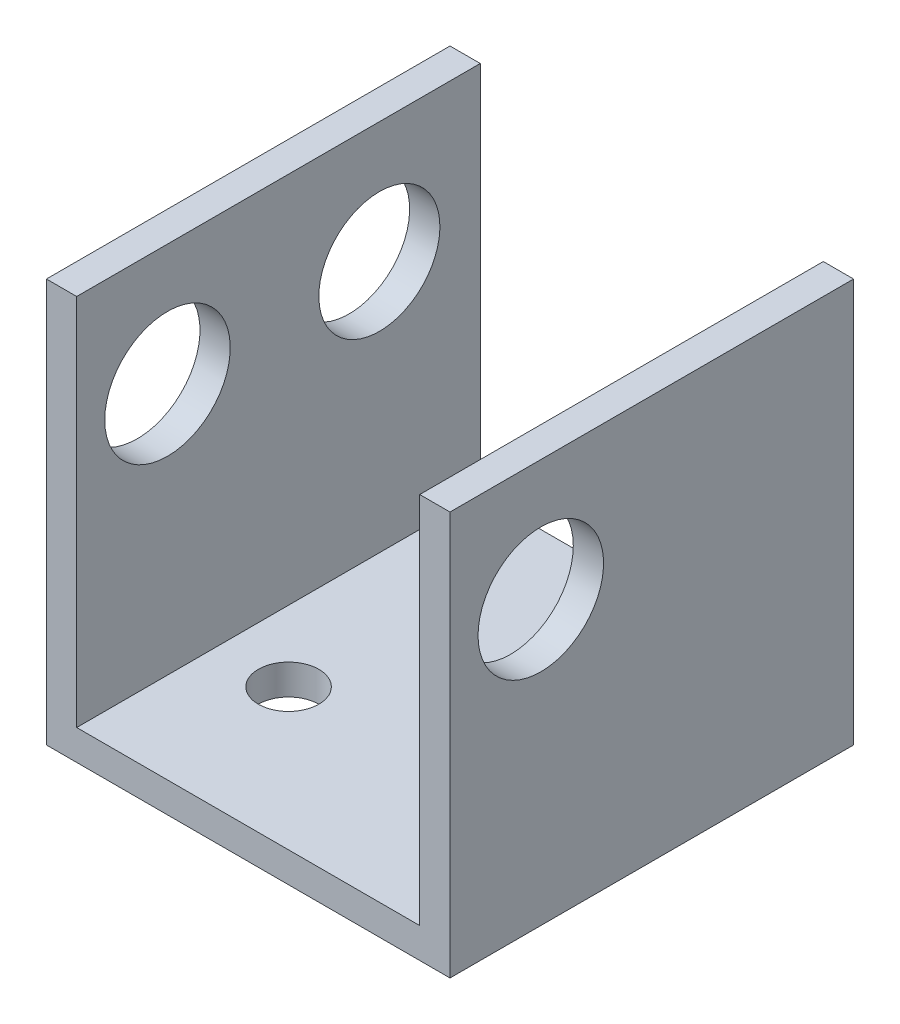
SolidWorks part; units mm, degrees
ref_plane "Plan de face" through (0, 0, 0) normal (0, 0, 1) x (1, 0, 0)
ref_plane "Plan de dessus" through (0, 0, 0) normal (0, 1, 0) x (1, 0, 0)
ref_plane "Plan de droite" through (0, 0, 0) normal (1, 0, 0) x (0, 0, -1)
sketch "Esquisse1" plane through (0, 0, 0) normal (0, 0, 1) x (1, 0, 0)
  line L0 (-31.1486, 3.3838) -> (-29.6486, 3.3838)
  line L1 (-29.6486, 3.3838) -> (-29.6486, -15.1162)
  line L2 (-29.6486, -15.1162) -> (-12.6486, -15.1162)
  line L3 (-11.1486, 3.3838) -> (-11.1486, -16.6162)
  line L4 (-11.1486, -16.6162) -> (-31.1486, -16.6162)
  line L5 (-31.1486, -16.6162) -> (-31.1486, 3.3838)
  line L6 (-12.6486, -15.1162) -> (-12.6486, 3.3838)
  line L7 (-12.6486, 3.3838) -> (-11.1486, 3.3838)
  dimension "D1" = 20
  dimension "D2" = 1.5
  dimension "D3" = 1.5
  dimension "D4" = 20
  dimension "D5" = 1.5
  dimension "D6" = 20
extrude "Extrusion1" add sketch "Esquisse1" along normal blind 20
sketch "Esquisse2" plane through (0, -15.1162, 0) normal (0, 1, 0) x (-1, 0, 0)
  line L1 (31.1486, 20) -> (31.1486, 0) construction
  line L2 (12.6486, 20) -> (29.6486, 20) construction
  line L4 (12.6486, 0) -> (29.6486, 0) construction
  line L5 (11.1486, 20) -> (11.1486, 0) construction
  circle A0 centre (26.1486, 13) radius 1.5
  circle A2 centre (16.1486, 7) radius 1.5
  dimension "D4" = 7
  dimension "D1" = 5
  dimension "D2" = 5
  dimension "D3" = 7
extrude "Extrusion2" cut sketch "Esquisse2" against normal through all
sketch "Esquisse4" plane through (-29.6486, 0, 0) normal (1, 0, 0) x (0, 0, -1)
  line L3 (0, -15.1162) -> (0, 3.3838) construction
  line L4 (-20, 3.3838) -> (0, 3.3838) construction
  circle A0 centre (-5, -2.6162) radius 3
  dimension "D1" = 5
  dimension "D2" = 6
extrude "Extrusion3" cut sketch "Esquisse4" against normal through all
sketch "Esquisse5" plane through (-31.1486, 0, 0) normal (-1, 0, 0) x (0, 0, 1)
  line L0 (20, 3.3838) -> (0, 3.3838) construction
  line L1 (20, 3.3838) -> (20, -16.6162) construction
  circle A0 centre (15.5, -2.6162) radius 3.11
  dimension "D1" = 6
  dimension "D2" = 4.5
extrude "Extrusion4" cut sketch "Esquisse5" against normal through all
